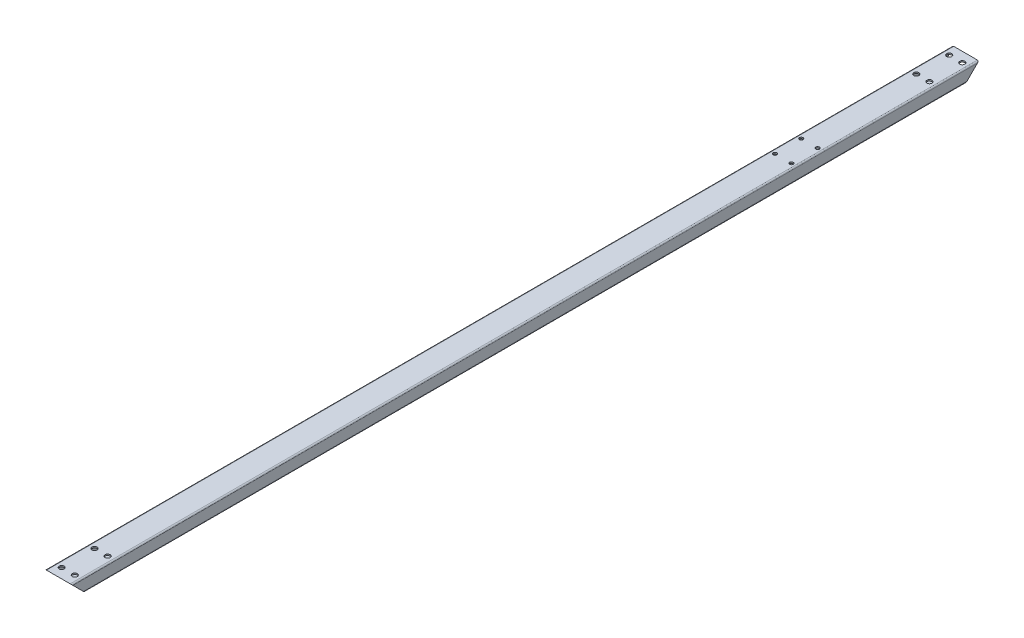
SolidWorks part; units mm, degrees
material "1.4003 (X2CrNi12)"
ref_plane "Ön Düzlem" through (0, 0, 0) normal (0, 0, 1) x (1, 0, 0)
ref_plane "Üst Düzlem" through (0, 0, 0) normal (0, 1, 0) x (1, 0, 0)
ref_plane "Sağ Düzlem" through (0, 0, 0) normal (1, 0, 0) x (0, 0, -1)
sketch "Çizim1" plane through (0, 0, 0) normal (0, 0, 1) x (1, 0, 0)
  line L0 (-36, 16) -> (-36, -16)
  line L1 (-36, 20) -> (36, 20)
  line L2 (-40, 16) -> (-40, -16)
  line L3 (-36, -20) -> (36, -20)
  line L4 (40, 16) -> (40, -16)
  line L5 (-40, 20) -> (40, -20) construction
  line L6 (-40, -20) -> (40, 20) construction
  line L7 (-36, -16) -> (36, -16)
  line L8 (36, 16) -> (36, -16)
  line L9 (-36, 16) -> (36, 16)
  line L10 (-40, 20) -> (40, 20) construction
  line L11 (40, 20) -> (40, -20) construction
  line L12 (-40, -20) -> (40, -20) construction
  line L13 (-40, 20) -> (-40, -20) construction
  arc A0 (36, 20) -> (40, 16) centre (36, 16) cw
  arc A1 (40, -16) -> (36, -20) centre (36, -16) cw
  arc A2 (-40, -16) -> (-36, -20) centre (-36, -16) ccw
  arc A3 (-36, 20) -> (-40, 16) centre (-36, 16) ccw
  point P0 (0, 0)
  dimension "D4" = 4
  dimension "D1" = 80
  dimension "D2" = 40
  dimension "D3" = 4
extrude "Yükseklik-Ekstrüzyon1" add sketch "Çizim1" along normal blind 1380 and the other way blind 1380
sketch "Çizim2" plane through (0, 20, 0) normal (0, 1, 0) x (1, 0, 0)
  line L0 (36, 1380) -> (-36, 1380) construction
  line L1 (-20, 1350) -> (20, 1350) construction
  line L2 (-20, 1350) -> (-20, 1250) construction
  line L3 (-20, 1250) -> (20, 1250) construction
  line L4 (20, 1350) -> (20, 1250) construction
  line L5 (-20, 1350) -> (20, 1250) construction
  line L6 (-20, 1250) -> (20, 1350) construction
  line L11 (-36, 0) -> (36, 0) construction
  line L12 (-36, 1380) -> (-36, -1380) construction
  line L13 (-40, 1380) -> (-40, -1380) construction
  line L15 (36, 1380) -> (36, -1380) construction
  line L16 (-20, -1250) -> (20, -1350) construction
  line L17 (-20, -1350) -> (20, -1250) construction
  line L18 (20, -1350) -> (20, -1250) construction
  line L19 (-20, -1250) -> (20, -1250) construction
  line L20 (-20, -1350) -> (-20, -1250) construction
  line L21 (-20, -1350) -> (20, -1350) construction
  circle A0 centre (-20, 1350) radius 7.75
  circle A1 centre (20, 1350) radius 7.75
  circle A2 centre (20, 1250) radius 7.75
  circle A3 centre (-20, 1250) radius 7.75
  circle A4 centre (-20, -1250) radius 7.75
  circle A5 centre (20, -1250) radius 7.75
  circle A6 centre (20, -1350) radius 7.75
  circle A7 centre (-20, -1350) radius 7.75
  point P0 (0, 1300)
  point P27 (0, -1300)
  dimension "D1" = 15.5
  dimension "D3" = 30
  dimension "D2" = 40
  dimension "D4" = 40
  dimension "D5" = 100
extrude "Kes-Ekstrüzyon1" cut sketch "Çizim2" against normal blind 10
sketch "Çizim3" plane through (0, 20, 0) normal (0, 1, 0) x (1, 0, 0)
  line L0 (40, 1380) -> (40, -1380) construction
  line L1 (25, 905) -> (-25, 905) construction
  line L2 (25, 905) -> (25, 825) construction
  line L3 (25, 825) -> (-25, 825) construction
  line L4 (-25, 905) -> (-25, 825) construction
  line L5 (25, 905) -> (-25, 825) construction
  line L6 (25, 825) -> (-25, 905) construction
  line L7 (36, 1380) -> (-36, 1380) construction
  circle A0 centre (25, 905) radius 5.5
  circle A1 centre (-25, 905) radius 5.5
  circle A2 centre (25, 825) radius 5.5
  circle A3 centre (-25, 825) radius 5.5
  point P0 (0, 865)
  dimension "D5" = 11
  dimension "D6" = 11
  dimension "D7" = 11
  dimension "D8" = 11
  dimension "D1" = 80
  dimension "D2" = 50
  dimension "D3" = 40
  dimension "D4" = 515
extrude "Kes-Ekstrüzyon2" cut sketch "Çizim3" against normal blind 20
sketch "Çizim4" plane through (0, 0, -1380) normal (0, 0, -1) x (-1, 0, 0)
  line L1 (-36, 16) -> (36, 16)
  line L2 (-36, 16) -> (-36, -16)
  line L3 (-36, -16) -> (36, -16)
  line L4 (36, 16) -> (36, -16)
extrude "Yükseklik-Ekstrüzyon2" add sketch "Çizim4" against normal blind 5 separate body
sketch "Çizim5" plane through (0, 0, 1380) normal (0, 0, 1) x (1, 0, 0)
  line L1 (-36, 16) -> (36, 16)
  line L2 (-36, 16) -> (-36, -16)
  line L3 (-36, -16) -> (36, -16)
  line L4 (36, 16) -> (36, -16)
extrude "Yükseklik-Ekstrüzyon3" add sketch "Çizim5" against normal blind 5 separate body
sketch "Çizim6" plane through (0, 0, 0) normal (1, 0, 0) x (0, 0, -1)
  line L7 (-1380, -20) -> (-1380, 20)
  line L8 (-1380, 20) -> (-1340, -20)
  line L9 (1380, -20) -> (-1380, -20) construction
  line L10 (-1340, -20) -> (-1380, -20)
  line L11 (1380, -20) -> (1340, -20)
  line L12 (1340, -20) -> (1380, 20)
  line L13 (1380, 20) -> (1380, -20)
  dimension "D1" = 45
  dimension "D2" = 45
extrude "Kes-Ekstrüzyon3" cut sketch "Çizim6" against normal blind 290 and the other way blind 220
